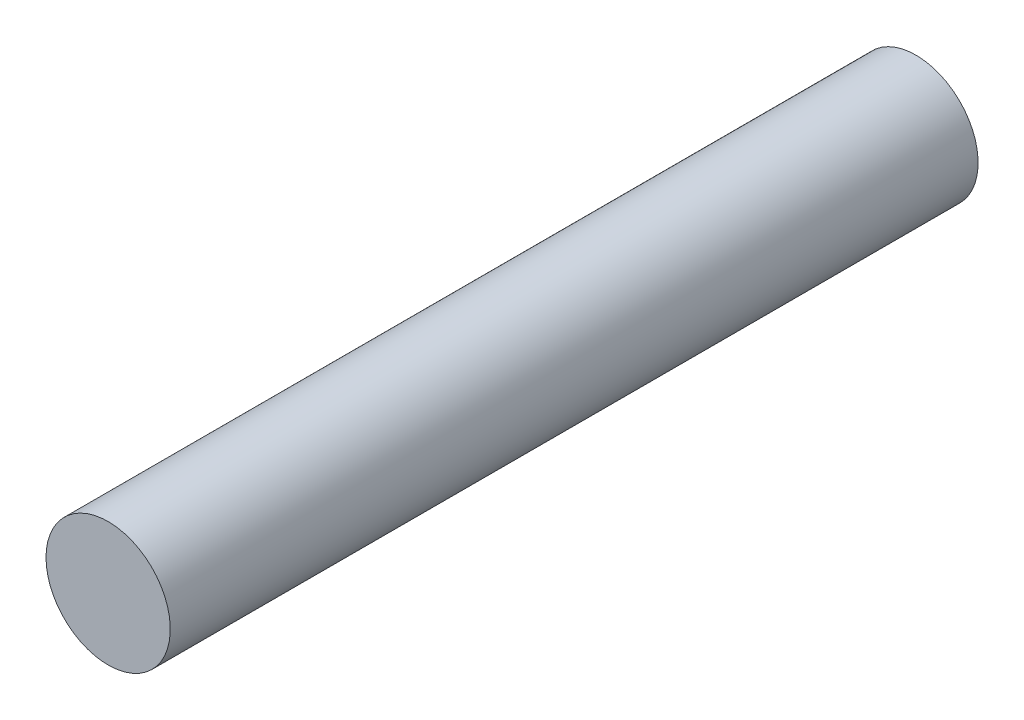
SolidWorks part; units mm, degrees
ref_plane "Piano frontale" through (0, 0, 0) normal (0, 0, 1) x (1, 0, 0)
ref_plane "Piano superiore" through (0, 0, 0) normal (0, 1, 0) x (1, 0, 0)
ref_plane "Piano destro" through (0, 0, 0) normal (1, 0, 0) x (0, 0, -1)
sketch "Schizzo1" plane through (0, 0, 0) normal (0, 0, 1) x (1, 0, 0)
  circle A0 centre (0, 0) radius 1
  dimension "D1" = 2
extrude "Estrusione-Estrusione1" add sketch "Schizzo1" along normal blind 13
